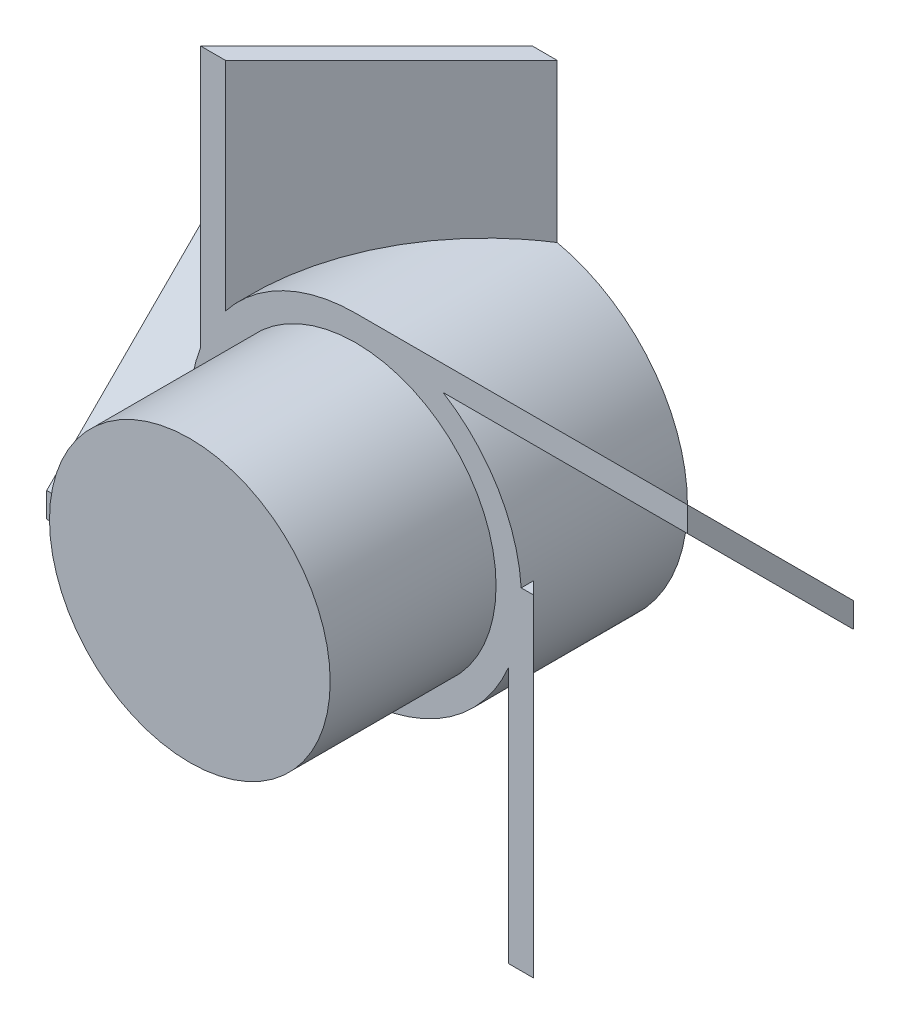
SolidWorks part; units mm, degrees
ref_plane "Front Plane" through (0, 0, 0) normal (0, 0, 1) x (1, 0, 0)
ref_plane "Top Plane" through (0, 0, 0) normal (0, 1, 0) x (1, 0, 0)
ref_plane "Right Plane" through (0, 0, 0) normal (1, 0, 0) x (0, 0, -1)
sketch "Sketch1" plane through (0, 0, 0) normal (0, 0, 1) x (1, 0, 0)
  circle A0 centre (0, 0) radius 10
  circle A1 centre (0, 0) radius 20
  dimension "D1" = 20
  dimension "D2" = 40
extrude "Boss-Extrude1" add sketch "Sketch1" along normal mid plane 20
sketch "Sketch2" plane through (0, 0, 0) normal (1, 0, 0) x (0, 0, -1)
  line L0 (-10, 20) -> (-10, 60)
  line L1 (10, 20) -> (-10, 20) construction
  line L2 (-10, 60) -> (-8.5, 60)
  line L3 (-8.5, 60) -> (-8.5, 20)
  line L4 (-8.5, 20) -> (-10, 20)
  line L5 (-10, 20) -> (-10, -20) construction
  dimension "D1" = 40
  dimension "D2" = 90
  dimension "D3" = 0
  dimension "D4" = 1.5
sketch "Sketch4" plane through (0, 0, 0) normal (0, 1, 0) x (1, 0, 0)
  line L0 (20, -10) -> (20, 10) construction
  line L1 (20, 8) -> (60, 8)
  line L2 (20, 8) -> (20, 10)
  line L3 (20, 10) -> (60, 10)
  line L4 (60, 8) -> (60, 10)
  line L6 (20, 10) -> (-20, 10) construction
  dimension "D1" = 90
  dimension "D2" = 40
  dimension "D3" = 2
sketch "Sketch5" plane through (0, 0, 10) normal (0, 0, 1) x (1, 0, 0)
  circle A0 centre (0, 0) radius 16.925
  dimension "D1" = 33.85
extrude "Boss-Extrude2" add sketch "Sketch5" along normal mid plane 40 contours A0
sketch "Sketch6" plane through (0, 0, 0) normal (1, 0, 0) x (0, 0, -1)
  line L0 (10, 0) -> (-10, 20)
  line L1 (10, -20) -> (10, 20) construction
  line L2 (-10, 20) -> (-10, -20) construction
  line L3 (10, 0) -> (-13.4815, 0) construction
  line L4 (-10, 20) -> (-10, 17)
  line L5 (10, 0) -> (10, -3)
  line L6 (-10, 17) -> (10, -3)
  dimension "D1" = 45
  dimension "D2" = 3
  dimension "D3" = 3
extrude "Boss-Extrude3" add sketch "Sketch6" along normal blind 40
pattern_circular "CirPattern1" count 4 every 90 about axis through (1.3703, -0.0687, 0) along (0, 0, 1) of "Boss-Extrude3"
